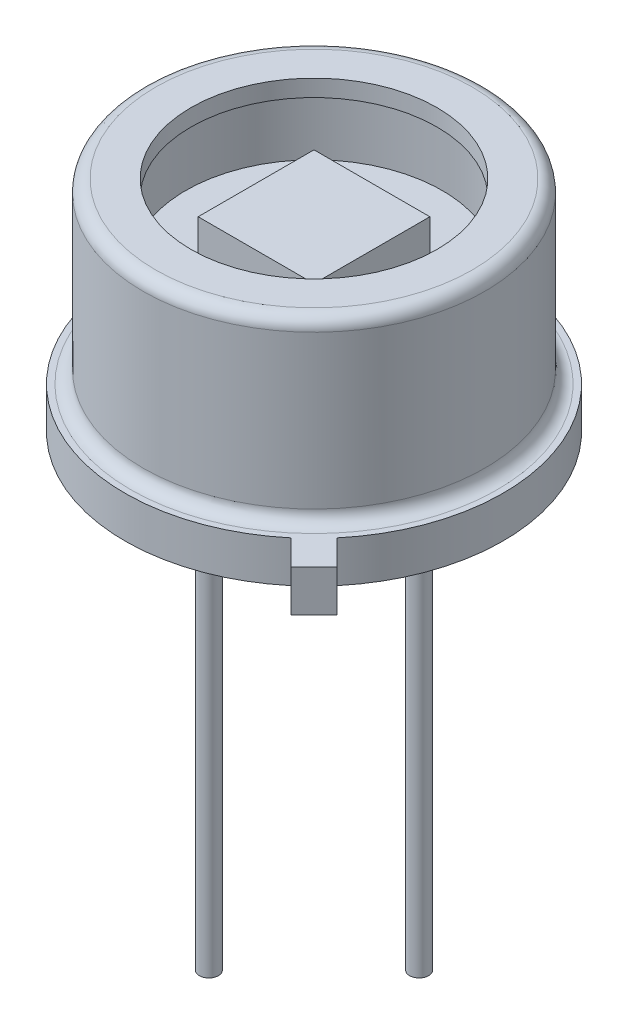
SolidWorks part; units mm, degrees
material "2.0060 (Cu-ETP)"
ref_plane "Front" through (0, 0, 0) normal (0, 0, 1) x (1, 0, 0)
ref_plane "Top" through (0, 0, 0) normal (0, 1, 0) x (1, 0, 0)
ref_plane "Right" through (0, 0, 0) normal (1, 0, 0) x (0, 0, -1)
sketch "Sketch1" plane through (0, 0, 0) normal (0, 1, 0) x (1, 0, 0)
  line L0 (2.9425, -3.4993) -> (3.5532, -4.1099)
  line L1 (3.5532, -4.1099) -> (4.1099, -3.5532)
  line L2 (4.1099, -3.5532) -> (3.4993, -2.9425)
  line L3 (0, 0) -> (3.8315, -3.8315) construction
  line L4 (0, 0) -> (0, -4.572) construction
  arc A0 (3.4993, -2.9425) -> (2.9425, -3.4993) centre (0, 0) ccw
  dimension "D1" = 4.572
  dimension "D2" = 0.7874
  dimension "D3" = 0.8636
  dimension "D4" = 45
extrude "Boss-Extrude1" add sketch "Sketch1" against normal blind 1
ref_plane "Plane2" through (0, 0, -0.96) normal (0, 0, -1) x (-1, 0, 0)
sketch "Sketch5" plane through (0, 0, 0) normal (0, 0, 1) x (1, 0, 0)
  line L0 (4.1275, 4.3) -> (2.9718, 4.3)
  line L1 (3.7211, 0.8936) -> (0, 0.8936)
  line L2 (0, 0) -> (4.1275, 0)
  line L3 (4.1275, 0) -> (4.1275, 4.3)
  line L4 (0, 0.8936) -> (0, 0)
  line L6 (2.9718, 4.3) -> (2.9718, 3.8936)
  line L7 (2.9718, 3.8936) -> (3.7211, 3.8936)
  line L8 (3.7211, 3.8936) -> (3.7211, 0.8936)
  dimension "D1" = 4.1275
  dimension "D2" = 4.3
  dimension "D3" = 0.4064
  dimension "D4" = 0.4064
  dimension "D5" = 2.9718
  dimension "D6" = 3
revolve "Revolve4" add sketch "Sketch5" angle 360 about L4
fillet "Fillet1" radius 0.3 2 edges at (0, 0, 4.1275) (4.1275, 4.3, 0)
sketch "Sketch6" plane through (0, -1, 0) normal (0, -1, 0) x (1, 0, 0)
  line L0 (0, 0) -> (3.8315, 3.8315) construction
  line L1 (3.5532, 4.1099) -> (4.1099, 3.5532) construction
  line L2 (0, 0) -> (2.23, -2.23) construction
  circle A1 centre (0, -2.54) radius 0.23
  circle A3 centre (0, 0) radius 2.54 construction
  circle A4 centre (-2.54, 0) radius 0.23
  circle A6 centre (0, 2.54) radius 0.23
  circle A8 centre (2.54, 0) radius 0.23
  dimension "D2" = 5.08
extrude "Boss-Extrude2" add sketch "Sketch6" along normal blind 10 and the other way blind 2.3
sketch "Эскиз2" plane through (0, 1.3, 0) normal (0, 1, 0) x (1, 0, 0)
  circle A0 centre (0, 0) radius 3.1
  dimension "D1" = 6.2
extrude "Бобышка-Вытянуть1" add sketch "Эскиз2" along normal blind 1.2
sketch "Эскиз3" plane through (0, 2.5, 0) normal (0, 1, 0) x (1, 0, 0)
  line L0 (0, 0) -> (0, 2.3166) construction
  line L1 (-1.4, 1.4) -> (1.4, 1.4)
  line L2 (-1.4, 1.4) -> (-1.4, -1.4)
  line L3 (-1.4, -1.4) -> (1.4, -1.4)
  line L4 (1.4, 1.4) -> (1.4, -1.4)
  line L5 (0, 0) -> (2.5623, 0) construction
  dimension "D1" = 1.4
  dimension "D2" = 2.8
  dimension "D3" = 2.8
  dimension "D4" = 1.4
extrude "Бобышка-Вытянуть2" add sketch "Эскиз3" along normal blind 1
